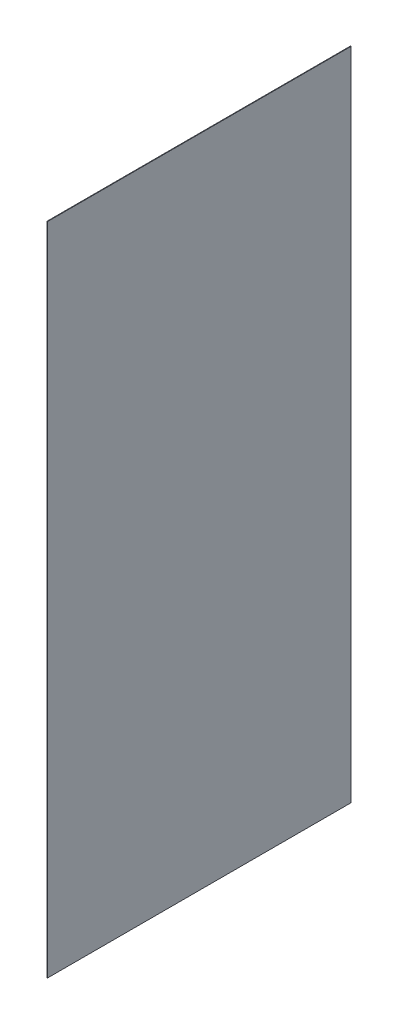
SolidWorks part; units mm, degrees
ref_plane "Front Plane" through (0, 0, 0) normal (0, 0, 1) x (1, 0, 0)
ref_plane "Top Plane" through (0, 0, 0) normal (0, 1, 0) x (1, 0, 0)
ref_plane "Right Plane" through (0, 0, 0) normal (1, 0, 0) x (0, 0, -1)
other "Configuration Table"
sketch "Sketch1" plane through (0, 0, 0) normal (0, 0, 1) x (1, 0, 0)
  line L1 (0, 200) -> (1.5, 200)
  line L2 (0, 200) -> (0, 1970)
  line L3 (0, 1970) -> (1.5, 1970)
  line L4 (1.5, 200) -> (1.5, 1970)
extrude "TOPPING_dis_yan_sol_1" add sketch "Sketch1" against normal blind 820 separate body
